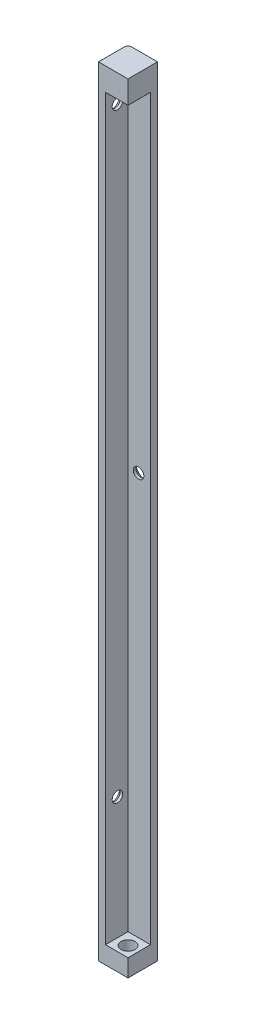
SolidWorks part; units mm, degrees
material "Aluminum"
ref_plane "Front Plane" through (0, 0, 0) normal (0, 0, 1) x (1, 0, 0)
ref_plane "Top Plane" through (0, 0, 0) normal (0, 1, 0) x (1, 0, 0)
ref_plane "Right Plane" through (0, 0, 0) normal (1, 0, 0) x (0, 0, -1)
sketch "Sketch1" plane through (0, 0, 0) normal (0, 1, 0) x (1, 0, 0)
  line L0 (0, 0) -> (0, 9)
  line L1 (0, 9) -> (9, 9)
  line L2 (2, 0) -> (2, 7)
  line L3 (2, 7) -> (9, 7)
  line L4 (9, 9) -> (9, 7)
  line L5 (0, 0) -> (2, 0)
  dimension "D1" = 9
  dimension "D2" = 9
  dimension "D3" = 2
extrude "Boss-Extrude1" add sketch "Sketch1" along normal blind 221.5
hole_wizard "CSK for M3 Countersunk Flat Head Screw1" positions "Sketch5" profile "Sketch4" countersink size "M3" standard "ISO" end condition through all
sketch "Sketch5" plane through (0, 0, 0) normal (-1, 0, 0) x (0, 0, 1)
  line L10 (0, 110.75) -> (-17.8047, 110.75) construction
  line L11 (0, 221.5) -> (0, 0) construction
  point P45 (-4, 211)
  point P49 (-4, 40.25)
sketch "Sketch4" plane through (0, 211, -4) normal (0, 1, 0) x (0, 0, 1)
  line L0 (0, 0) -> (0, 9)
  line L1 (0, 9) -> (1.5, 9)
  line L2 (1.5, 9) -> (1.5, 1.25)
  line L3 (1.5, 1.25) -> (2.75, 0)
  line L5 (2.75, 0) -> (0, 0)
  line L6 (-1.5, 1.25) -> (-2.75, 0) construction
  line L11 (0, -6.35) -> (0, 107.95) construction
  dimension "Thru Hole Dia." = 3
  dimension "Thru Hole Depth" = 9
  dimension "Near C'Sink Dia." = 5.5
  dimension "Near C'Sink Angle" = 90
hole_wizard "CSK for M3 Countersunk Flat Head Screw4" positions "Sketch11" profile "Sketch10" countersink size "M3" standard "ISO" end condition through all
sketch "Sketch11" plane through (0, 0, -9) normal (0, 0, -1) x (-1, 0, 0)
  line L4 (0, 221.5) -> (0, 0) construction
  line L5 (-9, 110.75) -> (-28.0227, 110.75) construction
  line L6 (-9, 221.5) -> (-9, 0) construction
  point P2 (-5, 120)
  dimension "D1" = 9.25
  dimension "D3" = 5
sketch "Sketch10" plane through (5, 120, -9) normal (1, 0, 0) x (0, 1, 0)
  line L0 (0, 0) -> (0, 9)
  line L1 (0, 9) -> (1.5, 9)
  line L2 (1.5, 9) -> (1.5, 1.25)
  line L3 (1.5, 1.25) -> (2.75, 0)
  line L5 (2.75, 0) -> (0, 0)
  line L6 (-1.5, 1.25) -> (-2.75, 0) construction
  line L11 (0, -6.35) -> (0, 107.95) construction
  dimension "Thru Hole Dia." = 3
  dimension "Thru Hole Depth" = 9
  dimension "Near C'Sink Dia." = 5.5
  dimension "Near C'Sink Angle" = 90
sketch "Sketch12" plane through (0, 0, 0) normal (0, -1, 0) x (1, 0, 0)
  line L0 (2, -7) -> (9, -7) construction
  line L1 (1, -7) -> (9, -7)
  line L2 (1, -7) -> (1, 0)
  line L3 (1, 0) -> (9, 0)
  line L4 (9, -7) -> (9, 0)
  line L5 (9, -7) -> (9, -9) construction
extrude "Boss-Extrude2" add sketch "Sketch12" against normal blind 5.5
sketch "Sketch13" plane through (0, 221.5, 0) normal (0, 1, 0) x (1, 0, 0)
  line L0 (0, 8) -> (1, 9)
  line L1 (0, 9) -> (0, 0) construction
  line L2 (9, 9) -> (0, 9) construction
  line L3 (0, 8) -> (0, 9)
  line L4 (0, 9) -> (1, 9)
  dimension "D1" = 1
  dimension "D2" = 1
extrude "Cut-Extrude1" cut sketch "Sketch13" against normal blind 359
sketch "Sketch14" plane through (0, 0, 0) normal (0, -1, 0) x (1, 0, 0)
  line L0 (0, 0) -> (9, 0)
  line L1 (9, 0) -> (9, -9)
  line L2 (9, -9) -> (1, -9)
  line L3 (1, -9) -> (0, -8)
  line L4 (0, -8) -> (0, 0)
extrude "Boss-Extrude3" add sketch "Sketch14" along normal blind 3
sketch "Sketch18" plane through (0, 221.5, 0) normal (0, 1, 0) x (1, 0, 0)
  line L1 (0, 0) -> (9, 0)
  line L2 (0, 0) -> (0, 8)
  line L3 (1, 9) -> (9, 9)
  line L4 (9, 0) -> (9, 9)
  line L5 (1, 9) -> (0, 8)
  dimension "D1" = 9
  dimension "D2" = 9
extrude "Boss-Extrude4" add sketch "Sketch18" along normal blind 2.5 and the other way blind 6
sketch "Sketch19" plane through (0, 0, -9) normal (0, 0, -1) x (-1, 0, 0)
  line L0 (-9, 224) -> (-9, -3) construction
  line L1 (-9, 222) -> (0, 222)
  line L2 (-9, 222) -> (-9, 224)
  line L3 (-9, 224) -> (0, 224)
  line L4 (0, 222) -> (0, 224)
  line L5 (-1, 224) -> (0, 224) construction
  dimension "D1" = 2
extrude "Cut-Extrude2" cut sketch "Sketch19" against normal blind 10
sketch "Sketch20" plane through (0, 0, 0) normal (-1, 0, 0) x (0, 0, 1)
  line L0 (0, 222) -> (0, -3) construction
  line L1 (0, 222) -> (-0.6, 222)
  line L2 (0, 222) -> (0, -3)
  line L3 (0, -3) -> (-0.6, -3)
  line L4 (-0.6, 222) -> (-0.6, -3)
  line L5 (0, -3) -> (-8, -3) construction
  dimension "D1" = 0.6
extrude "Cut-Extrude3" cut sketch "Sketch20" against normal blind 10
ref_plane "Plane1" through (1, 222, -9) normal (0, 1, 0) x (1, 0, 0)
sketch "Sketch22" plane through (0, 0, -9) normal (0, 0, -1) x (-1, 0, 0)
  line L0 (-9, 222) -> (-1, 222) construction
  line L1 (-9, 222) -> (-8.4, 222)
  line L2 (-9, 222) -> (-9, -3)
  line L3 (-9, -3) -> (-8.4, -3)
  line L4 (-8.4, 222) -> (-8.4, -3)
  line L5 (-1, -3) -> (-9, -3) construction
  dimension "D1" = 0.6
extrude "Cut-Extrude4" cut sketch "Sketch22" against normal blind 10
sketch "Sketch25" plane through (0, 0, 0) normal (-1, 0, 0) x (0, 0, 1)
  line L0 (-0.6, -3) -> (-8, -3) construction
  line L1 (-0.6, -3) -> (-9, -3)
  line L2 (-0.6, -3) -> (-0.6, 2.5)
  line L3 (-0.6, 2.5) -> (-9, 2.5)
  line L4 (-9, -3) -> (-9, 2.5)
  line L5 (-9, -3) -> (-9, 222) construction
  dimension "D1" = 5.5
extrude "Cut-Extrude5" cut sketch "Sketch25" against normal blind 10
sketch "Sketch29" plane through (0, 2.5, 0) normal (0, -1, 0) x (1, 0, 0)
  line L0 (8.4, -0.6) -> (0, -0.6)
  line L1 (0, -0.6) -> (0, -8)
  line L2 (0, -8) -> (1, -9)
  line L3 (1, -9) -> (8.4, -9)
  line L4 (8.4, -9) -> (8.4, -0.6)
extrude "Boss-Extrude5" add sketch "Sketch29" along normal blind 2
hole_wizard "Tap Drill for M4x0.7 Tap1" positions "Sketch31" profile "Sketch30" hole size "M4x0.7" standard "ANSI Metric"
sketch "Sketch31" plane through (0, 0.5, 0) normal (0, -1, 0) x (-1, 0, 0)
  point P0 (-5.4, 3.6)
sketch "Sketch30" plane through (5.4, 0.5, -3.6) normal (1, 0, 0) x (0, 0, -1)
  line L0 (0, 0) -> (0, 5)
  line L1 (0, 5) -> (2, 5)
  line L2 (2, 5) -> (2, 0)
  line L5 (2, 0) -> (0, 0)
  line L11 (0, -6.35) -> (0, 107.95) construction
  dimension "Thru Hole Dia." = 4
  dimension "Thru Hole Depth" = 5
sketch "Sketch32" plane through (0, 222, 0) normal (0, 1, 0) x (1, 0, 0)
  line L0 (1, 9) -> (0, 8)
  line L1 (0, 8) -> (0, 9)
  line L2 (0, 9) -> (1, 9)
extrude "Boss-Extrude6" add sketch "Sketch32" against normal blind 221.5
fillet "Fillet1" radius 1 1 edges at (0, 111.25, -9)
